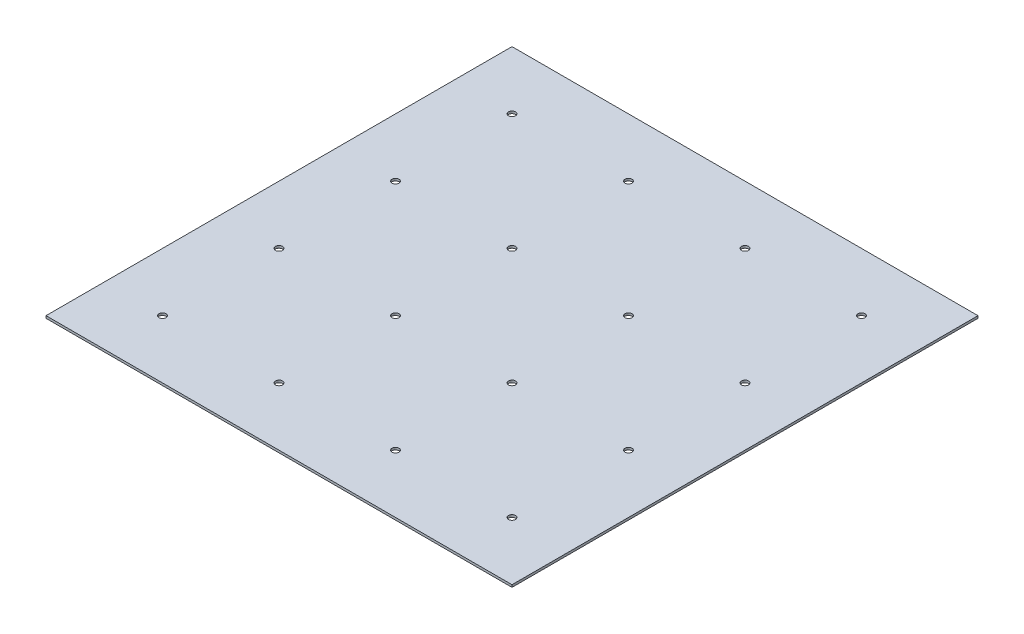
SolidWorks part; units mm, degrees
material "Stainless Steel (ferritic)"
ref_plane "Front Plane" through (0, 0, 0) normal (0, 0, 1) x (1, 0, 0)
ref_plane "Top Plane" through (0, 0, 0) normal (0, 1, 0) x (1, 0, 0)
ref_plane "Right Plane" through (0, 0, 0) normal (1, 0, 0) x (0, 0, -1)
sketch "Sketch1" plane through (0, 0, 0) normal (0, 1, 0) x (1, 0, 0)
  line L1 (-200, 200) -> (200, 200)
  line L2 (-200, 200) -> (-200, -200)
  line L3 (-200, -200) -> (200, -200)
  line L4 (200, 200) -> (200, -200)
  line L5 (-200, 200) -> (200, -200) construction
  line L6 (-200, -200) -> (200, 200) construction
  point P0 (0, 0)
  dimension "D1" = 400
  dimension "D2" = 400
extrude "Boss-Extrude1" add sketch "Sketch1" along normal blind 2
sketch "Sketch2" plane through (0, 2, 0) normal (0, 1, 0) x (1, 0, 0)
  line L0 (-200, 0) -> (200, 0) construction
  line L1 (-200, 200) -> (-200, -200) construction
  line L2 (200, -200) -> (200, 200) construction
  line L3 (0, 200) -> (0, -200) construction
  line L4 (200, 200) -> (-200, 200) construction
  line L5 (-200, -200) -> (200, -200) construction
  line L6 (-200, 150) -> (-150, 150) construction
  line L7 (-150, 150) -> (-150, 200) construction
  line L8 (-150, 150) -> (-50, 150) construction
  line L9 (-150, 150) -> (-150, 50) construction
  circle A0 centre (-150, 150) radius 3
  circle A1 centre (-50, 150) radius 3
  circle A2 centre (50, 150) radius 3
  circle A3 centre (150, 150) radius 3
  circle A4 centre (-50, 50) radius 3
  circle A5 centre (50, 50) radius 3
  circle A6 centre (150, 50) radius 3
  circle A7 centre (-50, -50) radius 3
  circle A8 centre (50, -50) radius 3
  circle A9 centre (150, -50) radius 3
  circle A10 centre (-50, -150) radius 3
  circle A11 centre (50, -150) radius 3
  circle A12 centre (150, -150) radius 3
  circle A13 centre (-150, 50) radius 3
  circle A14 centre (-150, -50) radius 3
  circle A15 centre (-150, -150) radius 3
  dimension "D2" = 6
  dimension "D1" = 50
  dimension "D5" = 90
  dimension "D6" = 100
  dimension "D7" = 100
  dimension "D3" = 4
  dimension "D4" = 4
extrude "Cut-Extrude1" cut sketch "Sketch2" against normal through all
